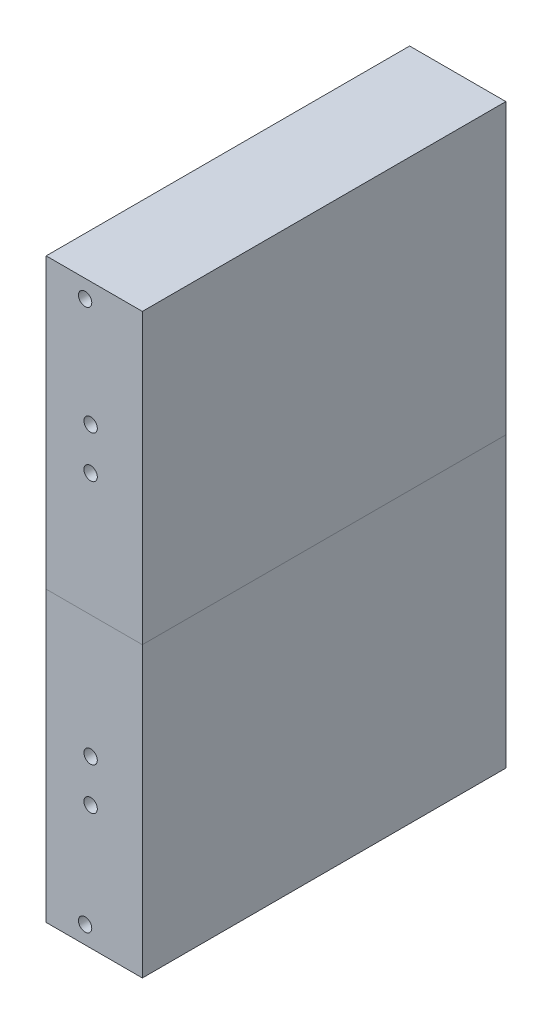
SolidWorks part; units mm, degrees
ref_plane "Front Plane" through (0, 0, 0) normal (0, 0, 1) x (1, 0, 0)
ref_plane "Top Plane" through (0, 0, 0) normal (0, 1, 0) x (1, 0, 0)
ref_plane "Right Plane" through (0, 0, 0) normal (1, 0, 0) x (0, 0, -1)
sketch "Sketch1" plane through (0, 0, 0) normal (0, 0, 1) x (1, 0, 0)
  line L1 (0, 0) -> (57.15, 0)
  line L2 (0, 0) -> (0, 171.45)
  line L3 (0, 171.45) -> (57.15, 171.45)
  line L4 (57.15, 0) -> (57.15, 171.45)
  dimension "D1" = 57.15
  dimension "D2" = 171.45
extrude "Boss-Extrude1" add sketch "Sketch1" along normal blind 215.9
sketch "Sketch2" plane through (0, 0, 0) normal (0, 0, -1) x (-1, 0, 0)
  circle A0 centre (-24.41, 70.569) radius 3.175 construction
  circle A1 centre (-24.41, 70.569) radius 3.175
extrude "Cut-Extrude1" cut sketch "Sketch2" against normal blind 46.74 contours A1
sketch "Sketch3" plane through (0, 0, 0) normal (0, 0, -1) x (-1, 0, 0)
  circle A0 centre (-24.41, 70.569) radius 3.9687 construction
  circle A1 centre (-24.41, 70.569) radius 3.9687
extrude "Cut-Extrude2" cut sketch "Sketch3" against normal blind 13.04 contours A1
sketch "Sketch4" plane through (0, 0, 215.9) normal (0, 0, 1) x (1, 0, 0)
  circle A1 centre (26.41, 73.569) radius 3.175 construction
  circle A2 centre (26.41, 98.569) radius 3.175 construction
  circle A4 centre (26.41, 73.569) radius 3.175
  circle A5 centre (26.41, 98.569) radius 3.175
extrude "Cut-Extrude3" cut sketch "Sketch4" against normal blind 35.16 contours A5 | A4
sketch "Sketch5" plane through (0, 0, 215.9) normal (0, 0, 1) x (1, 0, 0)
  circle A0 centre (23.13, 10.569) radius 3.175 construction
  circle A1 centre (23.13, 10.569) radius 3.175
extrude "Cut-Extrude4" cut sketch "Sketch5" against normal blind 94.66 contours A1
sketch "Sketch6" plane through (0, 0, 215.9) normal (0, 0, 1) x (1, 0, 0)
  circle A0 centre (26.41, 73.569) radius 3.9687 construction
  circle A1 centre (26.41, 98.569) radius 3.9687 construction
  circle A2 centre (26.41, 73.569) radius 3.9687
  circle A3 centre (26.41, 98.569) radius 3.9687
extrude "Cut-Extrude5" cut sketch "Sketch6" against normal blind 10.16 contours A3 | A2
sketch "Sketch7" plane through (0, 0, 215.9) normal (0, 0, 1) x (1, 0, 0)
  circle A0 centre (23.13, 10.569) radius 3.9687 construction
  circle A1 centre (23.13, 10.569) radius 3.9687
extrude "Cut-Extrude6" cut sketch "Sketch7" against normal blind 69.66 contours A1
sketch "Sketch8" plane through (0, 0, 0) normal (0, 0, -1) x (-1, 0, 0)
  point P0 (-57.15, 171.45)
mirror "Mirror2" about plane through (0, 171.45, 215.9) normal (0, -1, 0) of bodies 107
